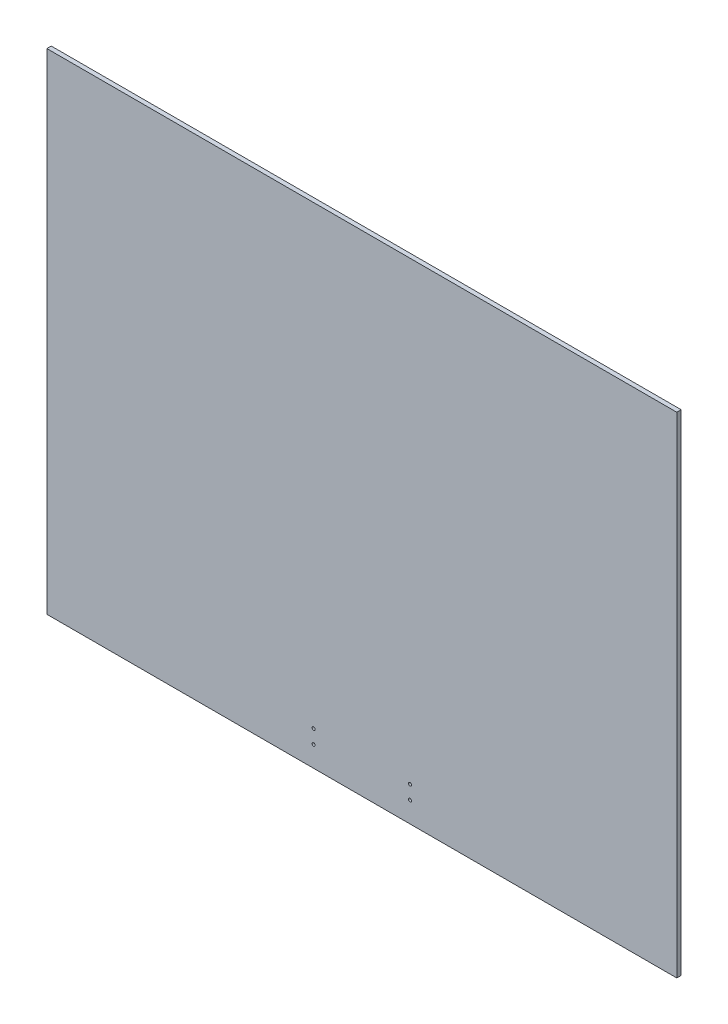
SolidWorks part; units mm, degrees
ref_plane "Front Plane" through (0, 0, 0) normal (0, 0, 1) x (1, 0, 0)
ref_plane "Top Plane" through (0, 0, 0) normal (0, 1, 0) x (1, 0, 0)
ref_plane "Right Plane" through (0, 0, 0) normal (1, 0, 0) x (0, 0, -1)
sketch "Sketch1" plane through (0, 0, 0) normal (0, 0, 1) x (1, 0, 0)
  line L1 (-457.2, -355.6) -> (457.2, -355.6)
  line L2 (-457.2, -355.6) -> (-457.2, 355.6)
  line L3 (-457.2, 355.6) -> (457.2, 355.6)
  line L4 (457.2, -355.6) -> (457.2, 355.6)
  line L5 (-457.2, -355.6) -> (457.2, 355.6) construction
  line L6 (-457.2, 355.6) -> (457.2, -355.6) construction
  point P0 (0, 0)
  dimension "D1" = 914.4
  dimension "D2" = 711.2
extrude "Boss-Extrude1" add sketch "Sketch1" along normal blind 6.35
sketch "Sketch2" plane through (0, 0, 6.35) normal (0, 0, 1) x (1, 0, 0)
  line L4 (457.2, -355.6) -> (457.2, 355.6)
  line L5 (457.2, 355.6) -> (-457.2, 355.6)
  line L6 (-457.2, 355.6) -> (-457.2, -355.6)
  line L7 (-457.2, -355.6) -> (457.2, -355.6)
  line L8 (457.2, -355.6) -> (457.2, 355.6)
  line L9 (457.2, 355.6) -> (-457.2, 355.6)
  line L10 (-457.2, 355.6) -> (-457.2, -355.6)
  line L11 (-457.2, -355.6) -> (457.2, -355.6)
  circle A0 centre (70, -305.6) radius 2.2 construction
  circle A1 centre (70, -325.6) radius 2.2 construction
  circle A2 centre (-70, -325.6) radius 2.2 construction
  circle A3 centre (-70, -305.6) radius 2.2 construction
  circle A4 centre (70, -305.6) radius 2.2
  circle A5 centre (70, -325.6) radius 2.2
  circle A6 centre (-70, -325.6) radius 2.2
  circle A7 centre (-70, -305.6) radius 2.2
  dimension "D1" = 0
extrude "Cut-Extrude2" cut sketch "Sketch2" against normal through all contours A4 | A5 | A7 | A6
